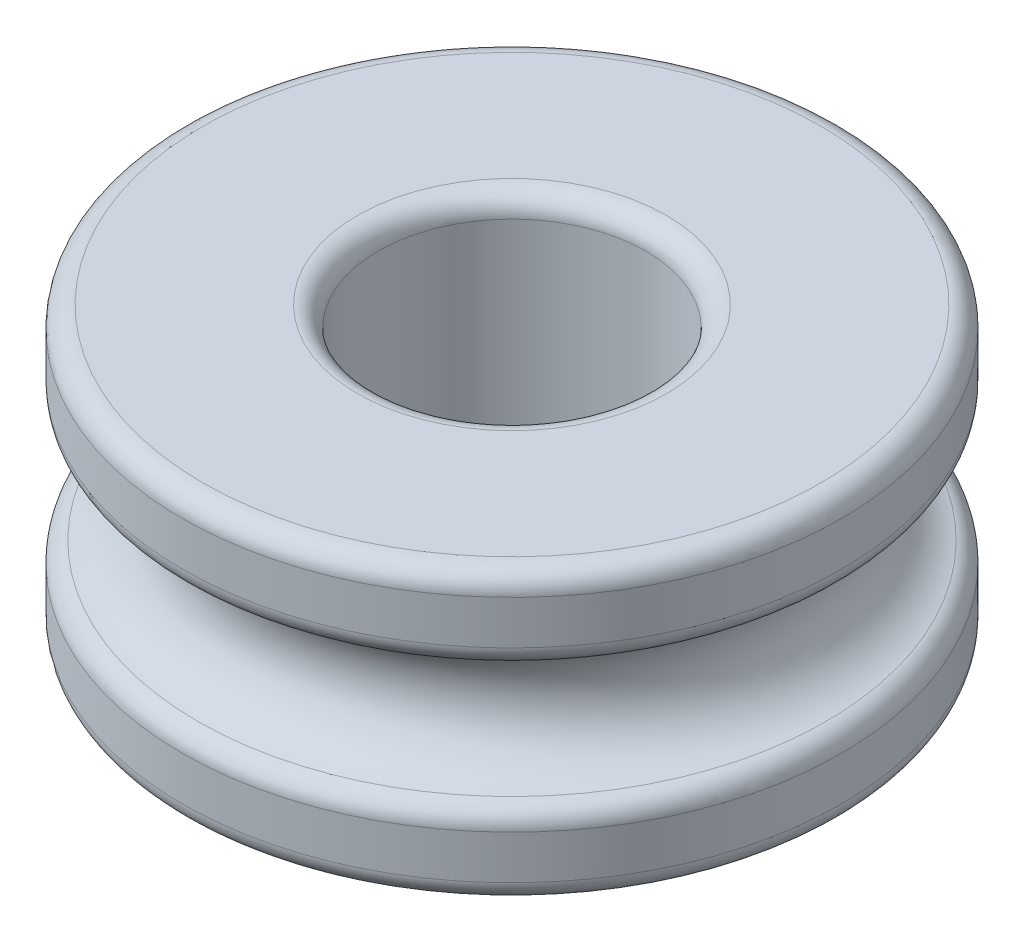
SolidWorks part; units mm, degrees
ref_plane "Front Plane" through (0, 0, 0) normal (0, 0, 1) x (1, 0, 0)
ref_plane "Top Plane" through (0, 0, 0) normal (0, 1, 0) x (1, 0, 0)
ref_plane "Right Plane" through (0, 0, 0) normal (1, 0, 0) x (0, 0, -1)
sketch "Sketch1" plane through (0, 0, 0) normal (0, 0, 1) x (1, 0, 0)
  line L0 (-1.625, 0) -> (6.375, 0) construction
  line L1 (-1.625, -3.5) -> (1.625, -3.5) construction
  line L2 (-1.625, -3.5) -> (-1.625, 3.5) construction
  line L3 (-1.625, 3.5) -> (1.625, 3.5) construction
  line L4 (1.625, -3.5) -> (1.625, 3.5)
  line L5 (-1.625, -3.5) -> (1.625, 3.5) construction
  line L6 (-1.625, 3.5) -> (1.625, -3.5) construction
  line L7 (6.375, 3.5) -> (6.375, -3.5) construction
  line L8 (1.625, 3.5) -> (6.375, 3.5)
  line L9 (1.625, 3.5) -> (1.625, -3.5)
  line L10 (1.625, -3.5) -> (6.375, -3.5)
  line L11 (6.375, 3.5) -> (6.375, 1.5)
  line L12 (6.375, -1) -> (6.375, -3.5)
  circle A7 centre (6.375, 0) radius 1.5
  point P0 (0, 0)
  point P18 (3.2, 0)
  dimension "D4" = 4.75
  dimension "D5" = 3
  dimension "D1" = 3.25
  dimension "D2" = 7
  dimension "D3" = 8
revolve "Revolve1" add sketch "Sketch1" angle 360 about L2
fillet "Fillet1" radius 0.5 6 edges at (-1.625, -3.5, -3.25) (-1.625, -3.5, -8) (-1.625, 3.5, -3.25) (-1.625, 3.5, -8) (-1.625, 1.5, -8) (-1.625, -1.5, -8)
